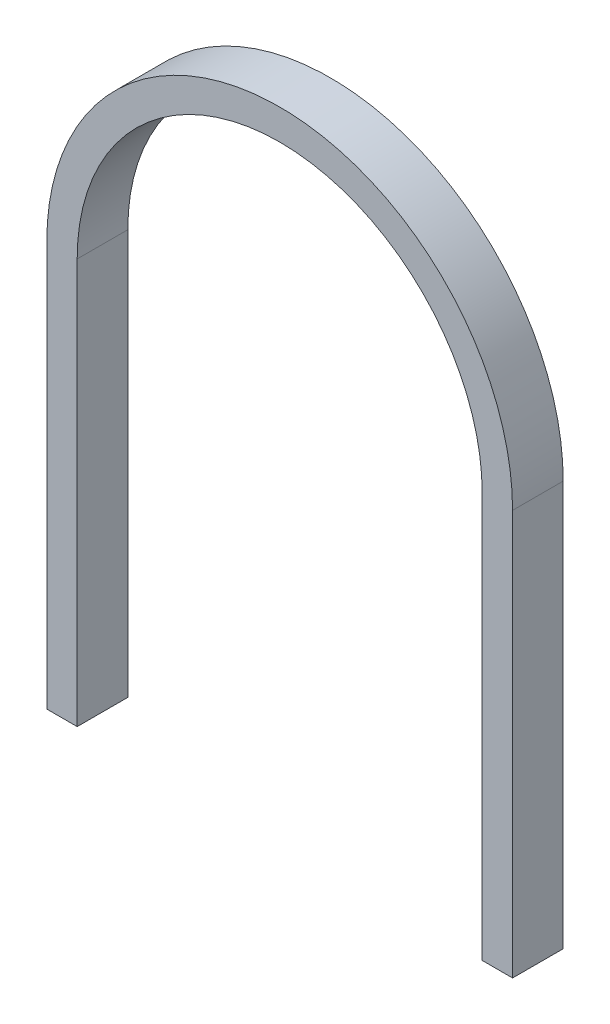
SolidWorks part; units mm, degrees
ref_plane "Plan de face" through (0, 0, 0) normal (0, 0, 1) x (1, 0, 0)
ref_plane "Plan de dessus" through (0, 0, 0) normal (0, 1, 0) x (1, 0, 0)
ref_plane "Plan de droite" through (0, 0, 0) normal (1, 0, 0) x (0, 0, -1)
sketch "Esquisse1" plane through (0, 0, 0) normal (0, 0, 1) x (1, 0, 0)
  line L0 (-20, 0) -> (-20, 40)
  line L1 (-20, 0) -> (-23, 0)
  line L2 (-23, 0) -> (-23, 40)
  line L3 (20, 40) -> (20, 0)
  line L4 (20, 0) -> (23, 0)
  line L5 (23, 0) -> (23, 40)
  line L6 (0, 0) -> (0, 36.8333) construction
  arc A0 (-20, 40) -> (20, 40) centre (0, 40) cw
  arc A1 (23, 40) -> (-23, 40) centre (0, 40) ccw
  point P13 (0, 0)
  point P14 (0, 0)
  point P15 (0, 60)
  dimension "D2" = 60
  dimension "D1" = 3
  dimension "D3" = 40
extrude "Boss.-Extru.1" add sketch "Esquisse1" along normal blind 5
